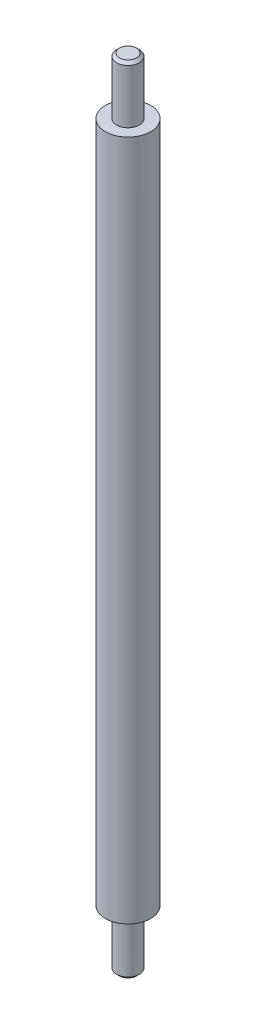
SolidWorks part; units mm, degrees
ref_plane "前视基准面" through (0, 0, 0) normal (0, 0, 1) x (1, 0, 0)
ref_plane "上视基准面" through (0, 0, 0) normal (0, 1, 0) x (1, 0, 0)
ref_plane "右视基准面" through (0, 0, 0) normal (1, 0, 0) x (0, 0, -1)
sketch "Sketch1" plane through (0, 0, 0) normal (0, 1, 0) x (1, 0, 0)
  circle A0 centre (0, 0) radius 4
extrude "Extrude1" add sketch "Sketch1" along normal blind 140
sketch "Sketch2" plane through (0, 140, 0) normal (0, 1, 0) x (1, 0, 0)
  circle A0 centre (0, 0) radius 2
  circle A1 centre (0, 0) radius 4
  circle A2 centre (0, 0) radius 4
  circle A3 centre (0, 0) radius 4 construction
  circle A4 centre (0, 0) radius 4
  circle A5 centre (0, 0) radius 4
  circle M2 centre (0, 0) radius 4
  dimension "D1" = 0
  dimension "D2" = 2
extrude "Extrude2" cut sketch "Sketch2" against normal blind 10 contours A0 M2
cosmetic thread "Cosmetic Thread1" parameters "D2"=3
sketch "Sketch3" plane through (0, 0, 0) normal (0, -1, 0) x (1, 0, 0)
  circle A0 centre (0, 0) radius 2
  circle A1 centre (0, 0) radius 4
  circle A2 centre (0, 0) radius 4
  dimension "D1" = 0
  dimension "D2" = 2
extrude "Extrude3" cut sketch "Sketch3" against normal blind 10
cosmetic thread "Cosmetic Thread2" parameters "D2"=3
chamfer "Chamfer1" distance 0.5 angle 45 2 edges at (0, 140, 2) (0, 0, -2)
